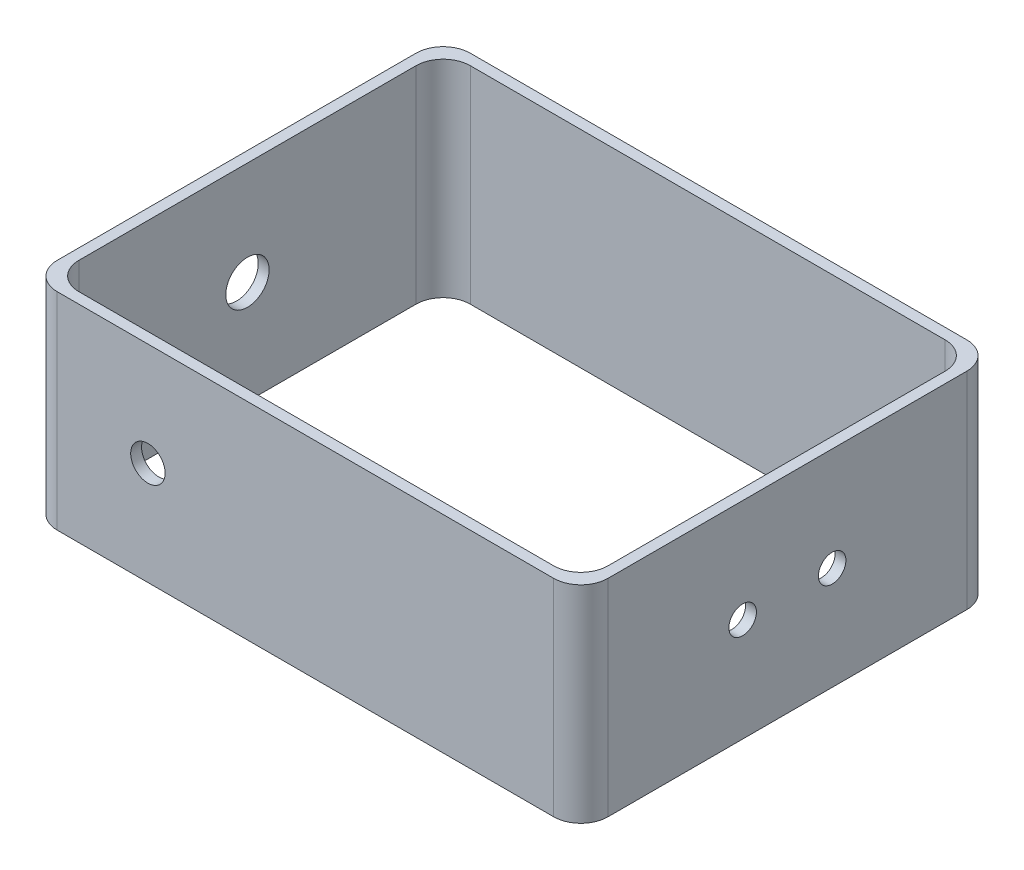
SolidWorks part; units mm, degrees
ref_plane "Front Plane" through (0, 0, 0) normal (0, 0, 1) x (1, 0, 0)
ref_plane "Top Plane" through (0, 0, 0) normal (0, 1, 0) x (1, 0, 0)
ref_plane "Right Plane" through (0, 0, 0) normal (1, 0, 0) x (0, 0, -1)
sketch "Sketch1" plane through (0, 0, 0) normal (0, 1, 0) x (1, 0, 0)
  line L1 (-50.8, 38.1) -> (50.8, 38.1)
  line L2 (-50.8, 38.1) -> (-50.8, -38.1)
  line L3 (-50.8, -38.1) -> (50.8, -38.1)
  line L4 (50.8, 38.1) -> (50.8, -38.1)
  line L5 (-50.8, 38.1) -> (50.8, -38.1) construction
  line L6 (-50.8, -38.1) -> (50.8, 38.1) construction
  point P0 (0, 0)
extrude "Boss-Extrude1" add sketch "Sketch1" along normal blind 38.1
sketch "Sketch3" plane through (0, 38.1, 0) normal (0, 1, 0) x (1, 0, 0)
  line L20 (48.8, -36.1) -> (48.8, 36.1)
  line L21 (-48.8, -36.1) -> (48.8, -36.1)
  line L22 (-48.8, 36.1) -> (-48.8, -36.1)
  line L23 (48.8, 36.1) -> (-48.8, 36.1)
  line L24 (48.8, -36.1) -> (48.8, 36.1)
  line L25 (-48.8, -36.1) -> (48.8, -36.1)
  line L26 (-48.8, 36.1) -> (-48.8, -36.1)
  line L27 (48.8, 36.1) -> (-48.8, 36.1)
  point P0 (0, 0)
  dimension "D1" = 2
extrude "Cut-Extrude1" cut sketch "Sketch3" against normal through all
sketch "Sketch5" plane through (50.8, 0, 0) normal (1, 0, 0) x (0, 0, -1)
  line L0 (0, 0) -> (0, 38.1) construction
  line L1 (-38.1, 0) -> (38.1, 0) construction
  line L2 (-38.1, 38.1) -> (38.1, 38.1) construction
  line L3 (0, 38.1) -> (-38.1, 0) construction
  line L4 (38.1, 0) -> (0, 38.1) construction
  line L5 (0, 0) -> (38.1, 38.1) construction
  line L6 (0, 0) -> (-38.1, 38.1) construction
  point P9 (-19.05, 19.05)
  point P15 (19.05, 19.05)
sketch "Sketch7" plane through (50.8, 0, 0) normal (1, 0, 0) x (0, 0, -1)
  circle A0 centre (-8.255, 19.05) radius 2.54
  circle A1 centre (8.255, 19.05) radius 2.54
extrude "Cut-Extrude2" cut sketch "Sketch7" against normal blind 2
sketch "Sketch9" plane through (-50.8, 0, 0) normal (-1, 0, 0) x (0, 0, 1)
  circle A0 centre (0, 19.05) radius 4
extrude "Cut-Extrude3" cut sketch "Sketch9" against normal blind 2
sketch "Sketch10" plane through (0, 0, 38.1) normal (0, 0, 1) x (1, 0, 0)
  line L0 (-50.8, 19.05) -> (50.8, 19.05) construction
  line L1 (-50.8, 38.1) -> (-50.8, 0) construction
  line L2 (50.8, 38.1) -> (50.8, 0) construction
sketch "Sketch11" plane through (0, 0, 38.1) normal (0, 0, 1) x (1, 0, 0)
  line L0 (-50.8, 19.05) -> (50.8, 19.05) construction
  circle A0 centre (-29.0612, 19.05) radius 3.175
extrude "Cut-Extrude4" cut sketch "Sketch11" against normal blind 2
fillet "Fillet1" radius 5 4 edges at (-50.8, 19.05, 38.1) (-50.8, 19.05, -38.1) (50.8, 19.05, -38.1) (50.8, 19.05, 38.1)
fillet "Fillet2" radius 5 4 edges at (48.8, 19.05, -36.1) (48.8, 19.05, 36.1) (-48.8, 19.05, -36.1) (-48.8, 19.05, 36.1)
sketch "Sketch12" [suppressed] plane through (0, 0, 0) normal (0, -1, 0) x (1, 0, 0)
  text T0 "ΔΣ" font "Century Gothic" height in points 60
extrude "Cut-Extrude5" [suppressed] cut sketch "Sketch12" against normal blind 1
